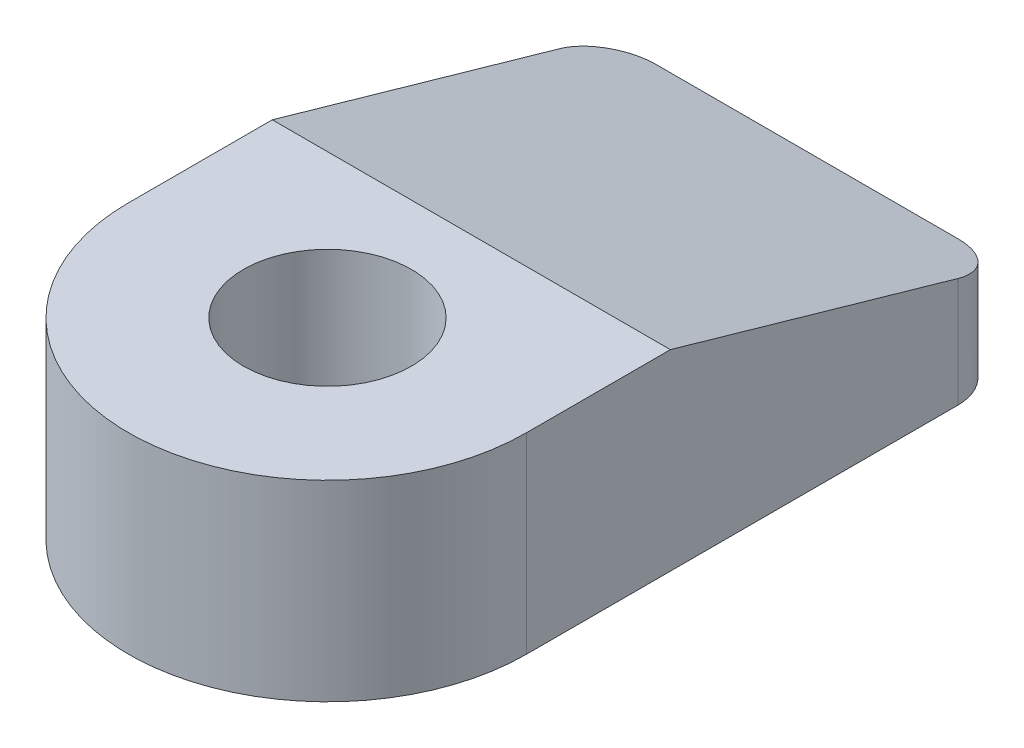
SolidWorks part; units mm, degrees
material "S235JR"
ref_plane "Piano X" through (0, 0, 0) normal (0, 0, 1) x (1, 0, 0)
ref_plane "Piano Y" through (0, 0, 0) normal (0, 1, 0) x (1, 0, 0)
ref_plane "Piano Z" through (0, 0, 0) normal (1, 0, 0) x (0, 0, -1)
sketch "Schizzo1" plane through (0, 0, 0) normal (0, 1, 0) x (1, 0, 0)
  line L0 (-4.15, 0) -> (-4.15, 10)
  line L1 (-4.15, 10) -> (4.15, 10)
  line L2 (4.15, 10) -> (4.15, 0)
  circle A0 centre (0, 0) radius 1.75
  arc A1 (-4.15, 0) -> (4.15, 0) centre (0, 0) ccw
  dimension "D1" = 3.5
  dimension "D3" = 10
  dimension "D2" = 2.4
extrude "Estrusione-Estrusione1" add sketch "Schizzo1" along normal blind 4
sketch "Schizzo2" plane through (4.15, 0, 0) normal (1, 0, 0) x (0, 0, -1)
  line L0 (10, 2) -> (10, 4)
  line L1 (10, 4) -> (10, 0) construction
  line L2 (10, 4) -> (3, 4)
  line L3 (0, 4) -> (10, 4) construction
  line L4 (3, 4) -> (10, 2)
  line L6 (0, 4) -> (0, 0) construction
  dimension "D1" = 2
  dimension "D2" = 3
extrude "Taglio-Estrusione1" cut sketch "Schizzo2" against normal through all
fillet "Raccordo1" radius 1 2 edges at (-4.15, 1, -10) (4.15, 1, -10)
equation "\"D2@Schizzo1\"=0.4*6"
